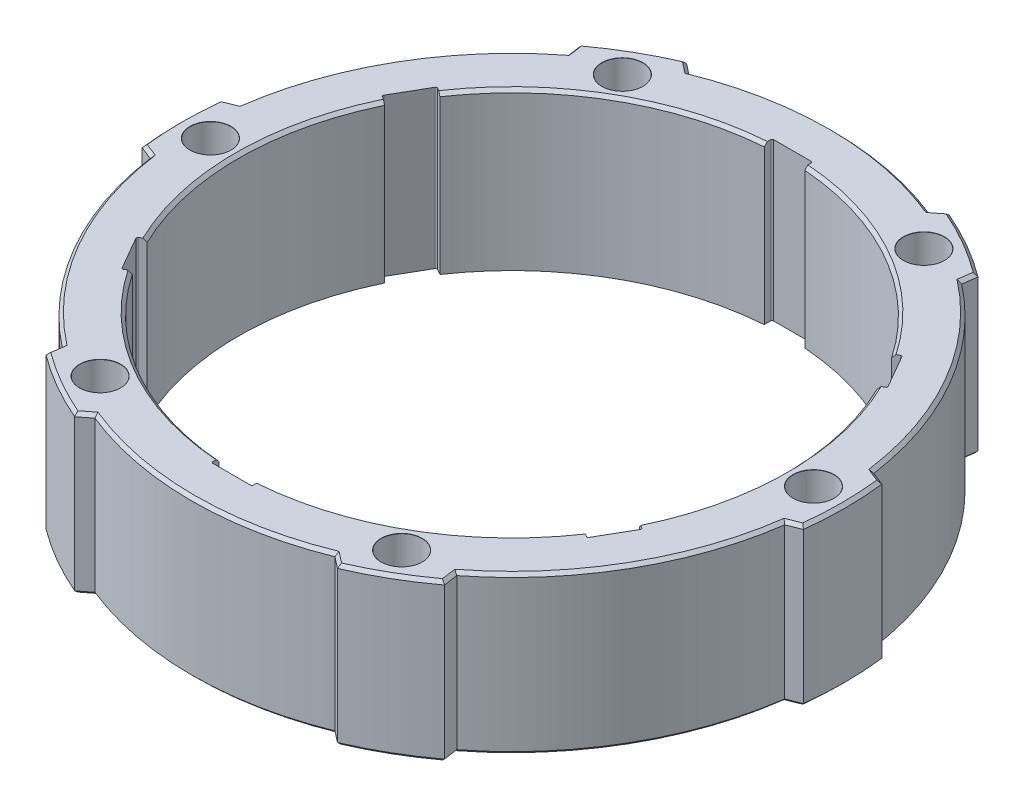
SolidWorks part; units mm, degrees
material "PET"
ref_plane "Front Plane" through (0, 0, 0) normal (0, 0, 1) x (1, 0, 0)
ref_plane "Top Plane" through (0, 0, 0) normal (0, 1, 0) x (1, 0, 0)
ref_plane "Right Plane" through (0, 0, 0) normal (1, 0, 0) x (0, 0, -1)
sketch "body_sketch" plane through (0, 0, 0) normal (0, 1, 0) x (1, 0, 0)
  circle A0 centre (0, 0) radius 53
  circle A1 centre (0, 0) radius 43.5
  dimension "D1" = 87
  dimension "D2" = 106
extrude "body" add sketch "body_sketch" along normal blind 25
sketch "hole_pos" plane through (0, 25, 0) normal (0, 1, 0) x (1, 0, 0)
  point P9 (48, 0)
  dimension "D1" = 48
hole_wizard "spring_screw_hole" positions "hole_pos" profile "Sketch4" counterbore size "M3" standard "DIN" end condition through all
sketch "Sketch4" plane through (48, 25, 0) normal (1, 0, 0) x (0, 0, 1)
  line L0 (0, 0) -> (0, 25)
  line L1 (0, 25) -> (1.7, 25)
  line L3 (1.7, 25) -> (1.7, 20)
  line L4 (3.25, 20) -> (1.7, 20)
  line L5 (3.25, 20) -> (3.25, 0.025)
  line L6 (3.25, 0.025) -> (3.275, 0)
  line L7 (3.275, 0) -> (0, 0)
  line L8 (-3.25, 0.025) -> (-3.275, 0) construction
  line L11 (0, -6.35) -> (0, 107.95) construction
  dimension "Thru Hole Depth" = 25
  dimension "C'Bore Depth" = 20
  dimension "Near C'Sink Angle" = 90
sketch "Sketch5" plane through (0, 25, 0) normal (0, 1, 0) x (1, 0, 0)
  line L10 (50.5037, 7.0978) -> (52.6316, 6.2381)
  line L11 (31.3987, 40.1885) -> (31.7181, 42.4613)
  line L12 (0, 0) -> (48, 0) construction
  arc A0 (50.5037, 7.0978) -> (31.3987, 40.1885) centre (0, 0) ccw
  circle A1 centre (48, 0) radius 1.7 construction
  circle A3 centre (0, 0) radius 53 construction
  arc A4 (31.7181, 42.4613) -> (52.6316, 6.2381) centre (0, 0) cw
  dimension "D3" = 51
  dimension "D4" = 22
  dimension "D5" = 82
  dimension "D1" = 8
  dimension "D2" = 44
extrude "side_cutouts" cut sketch "Sketch5" against normal through all
sketch "Sketch6" plane through (0, 25, 0) normal (0, 1, 0) x (1, 0, 0)
  line L0 (0, 0) -> (48, 0) construction
  line L1 (39.1804, 18.8984) -> (35.9567, 24.482)
  line L2 (35.9567, 24.482) -> (37.0392, 25.107)
  line L3 (37.0392, 25.107) -> (40.2629, 19.5234)
  line L4 (40.2629, 19.5234) -> (39.1804, 18.8984)
  line L5 (0, 0) -> (35.9567, 24.482) construction
  line L6 (0, 0) -> (39.1804, 18.8984) construction
  circle A0 centre (0, 0) radius 43.5 construction
  dimension "D1" = 25.75
  dimension "D2" = 8.5
  dimension "D3" = 1.25
extrude "driving_cutout" cut sketch "Sketch6" against normal through all
fillet "driving_cutout_fillet" radius 0.25 2 edges at (40.2629, 12.5, -19.5234) (37.0392, 12.5, -25.107)
pattern_circular "main_pattern" count 6 over 360 about axis through (0, 0, 0) along (0, 1, 0) of "spring_screw_hole", "side_cutouts", "driving_cutout", "driving_cutout_fillet"
chamfer "overall_chamfer" distance 0.5 angle 45 54 edges at (44.1673, 0, -25.5) (51.5676, 0, -6.668) (53, 0, 0) (51.5676, 0, 6.668) (44.1673, 0, 25.5) (31.5584, 0, 41.3249) (26.5, 0, 45.8993) (20.0092, 0, 47.9929) (0, 0, 51) (-20.0092, 0, 47.9929) (-26.5, 0, 45.8993) (-31.5584, 0, 41.3249) (-44.1673, 0, 25.5) (-51.5676, 0, 6.668) (-53, 0, 0) (-51.5676, 0, -6.668) (-44.1673, 0, -25.5) (-31.5584, 0, -41.3249) (-26.5, 0, -45.8993) (-20.0092, 0, -47.9929) (0, 0, -51) (20.0092, 0, -47.9929) (31.5584, 0, -41.3249) (26.5, 0, -45.8993) (31.5584, 25, 41.3249) (26.5, 25, 45.8993) (20.0092, 25, 47.9929) (0, 25, 51) (-20.0092, 25, 47.9929) (-26.5, 25, 45.8993) (-31.5584, 25, 41.3249) (-44.1673, 25, 25.5) (-51.5676, 25, 6.668) (-53, 25, 0) (-51.5676, 25, -6.668) (-44.1673, 25, -25.5) (-31.5584, 25, -41.3249) (-26.5, 25, -45.8993) (-20.0092, 25, -47.9929) (0, 25, -51) (20.0092, 25, -47.9929) (26.5, 25, -45.8993) (31.5584, 25, -41.3249) (44.1673, 25, -25.5) (51.5676, 25, -6.668) (53, 25, 0) (51.5676, 25, 6.668) (44.1673, 25, 25.5) (-43.5, 25, 0) (-21.75, 25, 37.6721) (21.75, 25, 37.6721) (43.5, 25, 0) (21.75, 25, -37.6721) (-21.75, 25, -37.6721)
equation "\"paper_size\" = 600mm"
equation "\"cb_roll_d_outer\" = 80mm"
equation "\"cb_roll_d_inner\" = 78mm"
equation "\"helper_d\" = 86mm"
equation "\"outer_d\" = 106mm"
equation "\"spring_l_max\" = 25mm"
equation "\"spring_l_min\" = 10mm"
equation "\"D2@body_sketch\"=\"outer_d\""
equation "\"D1@body_sketch\"=\"helper_d\" + 1"
equation "\"C'Bore Depth@Sketch4\"=\"spring_l_max\" - \"spring_l_min\" + 5"
equation "\"D3@Sketch5\"=\"outer_d\" / 2 - 2"
equation "\"D1@hole_pos\"=(\"outer_d\" + \"helper_d\") / 4"
